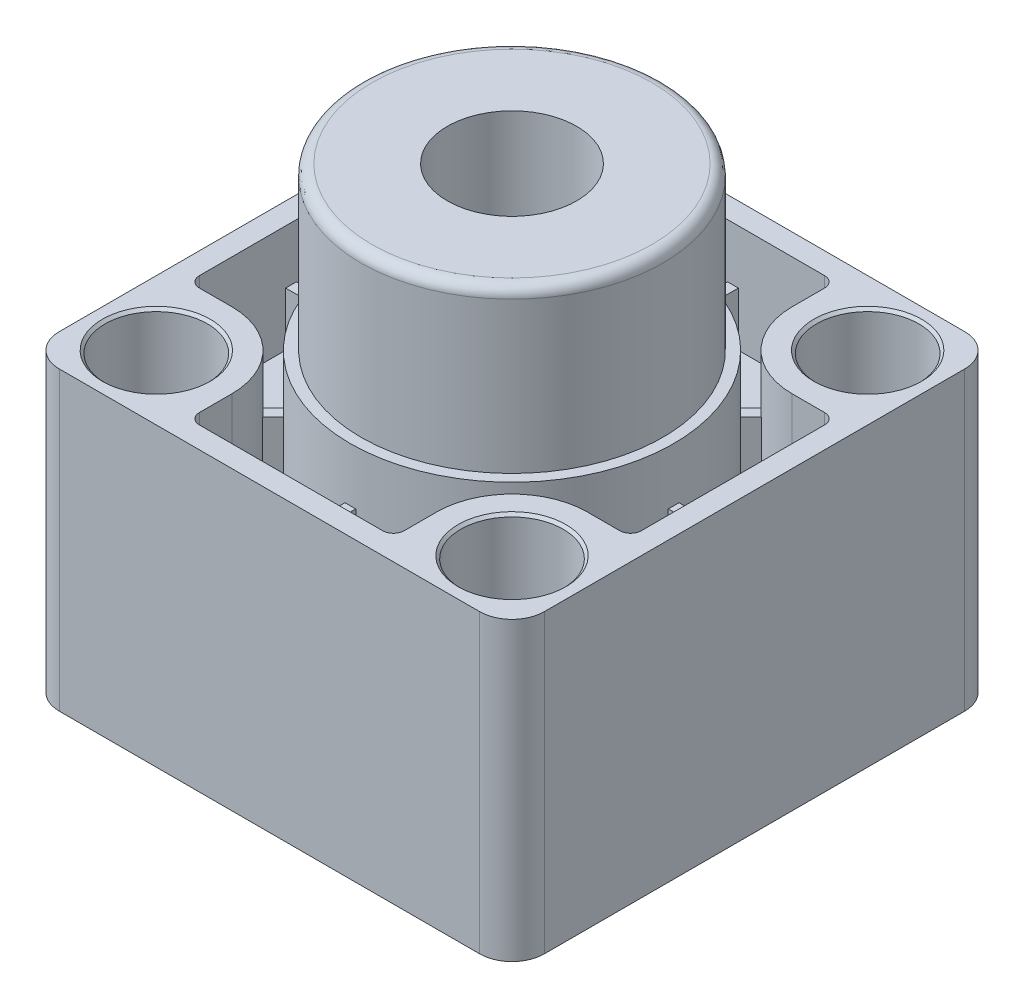
SolidWorks part; units mm, degrees
material "6061-T6 (SS)"
ref_plane "Front Plane" through (0, 0, 0) normal (0, 0, 1) x (1, 0, 0)
ref_plane "Top Plane" through (0, 0, 0) normal (0, 1, 0) x (1, 0, 0)
ref_plane "Right Plane" through (0, 0, 0) normal (1, 0, 0) x (0, 0, -1)
sketch "Sketch1" plane through (0, 0, 0) normal (0, 1, 0) x (1, 0, 0)
  line L1 (-19.5, -22.5) -> (19.5, -22.5)
  line L2 (-22.5, -19.5) -> (-22.5, 19.5)
  line L3 (-19.5, 22.5) -> (19.5, 22.5)
  line L4 (22.5, -19.5) -> (22.5, 19.5)
  line L5 (-22.5, -22.5) -> (22.5, 22.5) construction
  line L6 (-22.5, 22.5) -> (22.5, -22.5) construction
  arc A0 (-19.5, -22.5) -> (-22.5, -19.5) centre (-19.5, -19.5) cw
  arc A1 (19.5, -22.5) -> (22.5, -19.5) centre (19.5, -19.5) ccw
  arc A2 (19.5, 22.5) -> (22.5, 19.5) centre (19.5, 19.5) cw
  arc A3 (-22.5, 19.5) -> (-19.5, 22.5) centre (-19.5, 19.5) cw
  point P0 (0, 0)
  dimension "D2" = 3
  dimension "D1" = 45
extrude "Boss-Extrude1" add sketch "Sketch1" along normal blind 27.5
hole_wizard "CBORE for M6 Hex Socket Head Cap Screw1" positions "Sketch4" profile "Sketch3" counterbore size "M6" standard "DIN" end condition through all
sketch "Sketch4" plane through (0, 27.5, 0) normal (0, 1, 0) x (1, 0, 0)
  point P0 (-16.5, 16.5)
  point P2 (16.5, 16.5)
  point P4 (16.5, -16.5)
  point P6 (-16.5, -16.5)
  dimension "D1" = 33
  dimension "D2" = 16.5
  dimension "D3" = 16.5
  dimension "D4" = 16.5
sketch "Sketch3" plane through (-16.5, 27.5, -16.5) normal (1, 0, 0) x (0, 0, 1)
  line L0 (0, 0) -> (0, 27.5)
  line L1 (0, 27.5) -> (3.2, 27.5)
  line L3 (3.2, 27.5) -> (3.2, 15)
  line L4 (4.75, 15) -> (3.2, 15)
  line L5 (4.75, 15) -> (4.75, 0.25)
  line L6 (4.75, 0.25) -> (5, 0)
  line L7 (5, 0) -> (0, 0)
  line L8 (-4.75, 0.25) -> (-5, 0) construction
  line L11 (0, -6.35) -> (0, 107.95) construction
  dimension "Thru Hole Dia." = 6.4
  dimension "Thru Hole Depth" = 27.5
  dimension "C'Bore Dia." = 9.5
  dimension "C'Bore Depth" = 15
  dimension "Near C'Sink Dia." = 10
  dimension "Near C'Sink Angle" = 90
sketch "Sketch5" [suppressed] plane through (0, 27.5, 0) normal (0, 1, 0) x (1, 0, 0)
  line L4 (-9.5, 16.5) -> (-9.5, 20.5)
  line L5 (-16.5, 9.5) -> (-20.5, 9.5)
  line L6 (16.5, 9.5) -> (20.5, 9.5)
  line L7 (9.5, 16.5) -> (9.5, 20.5)
  line L8 (-19.5, -20.5) -> (19.5, -20.5)
  line L9 (20.5, -19.5) -> (20.5, 19.5)
  line L10 (19.5, 20.5) -> (-19.5, 20.5)
  line L11 (-20.5, 19.5) -> (-20.5, -19.5)
  line L12 (-19.5, -20.5) -> (19.5, -20.5)
  line L13 (20.5, -19.5) -> (20.5, 19.5)
  line L14 (19.5, 20.5) -> (-19.5, 20.5)
  line L15 (-20.5, 19.5) -> (-20.5, -19.5)
  line L16 (9.5, -16.5) -> (9.5, -20.5)
  line L17 (16.5, -9.5) -> (20.5, -9.5)
  line L18 (-16.5, -9.5) -> (-20.5, -9.5)
  line L19 (-9.5, -16.5) -> (-9.5, -20.5)
  circle A6 centre (-16.5, 16.5) radius 7
  arc A7 (-20.5, 10.7554) -> (-10.7554, 20.5) centre (-16.5, 16.5) ccw
  arc A8 (-20.5, -19.5) -> (-19.5, -20.5) centre (-19.5, -19.5) ccw
  arc A9 (19.5, -20.5) -> (20.5, -19.5) centre (19.5, -19.5) ccw
  arc A10 (20.5, 19.5) -> (19.5, 20.5) centre (19.5, 19.5) ccw
  arc A11 (-19.5, 20.5) -> (-20.5, 19.5) centre (-19.5, 19.5) ccw
  arc A12 (-20.5, -19.5) -> (-19.5, -20.5) centre (-19.5, -19.5) ccw
  arc A13 (19.5, -20.5) -> (20.5, -19.5) centre (19.5, -19.5) ccw
  arc A14 (20.5, 19.5) -> (19.5, 20.5) centre (19.5, 19.5) ccw
  arc A15 (-19.5, 20.5) -> (-20.5, 19.5) centre (-19.5, 19.5) ccw
  circle A39 centre (16.5, 16.5) radius 7
  arc A40 (10.7554, 20.5) -> (20.5, 10.7554) centre (16.5, 16.5) ccw
  circle A42 centre (-16.5, -16.5) radius 7
  arc A43 (-10.7554, -20.5) -> (-20.5, -10.7554) centre (-16.5, -16.5) ccw
  circle A44 centre (0, 0) radius 12
  circle A45 centre (16.5, -16.5) radius 7
  arc A46 (20.5, -10.7554) -> (10.7554, -20.5) centre (16.5, -16.5) ccw
  point P40 (0, 0)
  dimension "D7" = 24
  dimension "D6" = 4
  dimension "D1" = 2
  dimension "D2" = 2
  dimension "D3" = 2
  dimension "D4" = 2
  dimension "D5" = 2
extrude "Cut-Extrude1" [suppressed] cut sketch "Sketch5" against normal blind 10 contours A46 L17 L13 L6 A40 L7 L14 L4 A7 L5 L15 L18 A43 L19 L12 L16 A44
sketch "Sketch6" [suppressed] plane through (0, 17.5, 0) normal (0, 1, 0) x (1, 0, 0)
  line L0 (-20.5, 0) -> (12, 0)
  line L1 (-20.5, 9.5) -> (-20.5, -9.5) construction
  line L2 (0, 0) -> (0, 20.5)
  line L3 (9.5, 20.5) -> (-9.5, 20.5) construction
  line L4 (12, 0) -> (20.5, 0)
  line L5 (20.5, -9.5) -> (20.5, 9.5) construction
  line L6 (0, 0) -> (0, -20.5)
  line L7 (-9.5, -20.5) -> (9.5, -20.5) construction
  circle A1 centre (0, 0) radius 12 construction
extrude "Extrude-Thin2" [suppressed] add sketch "Sketch6" along normal blind 5 thin
draft "Draft1" [suppressed] type of draft neutral plane draft angle 4 faces to draft 1 parameters "D1"=4
sketch "Sketch7" [suppressed] plane through (0, 27.5, 0) normal (0, 1, 0) x (1, 0, 0)
  circle A2 centre (0, 0) radius 10
  circle A3 centre (0, 0) radius 10
  dimension "D1" = 2
extrude "Cut-Extrude2" [suppressed] cut sketch "Sketch7" against normal blind 1
sketch "Sketch8" plane through (0, 27.5, 0) normal (0, 1, 0) x (1, 0, 0)
  line L2 (-20.5, 19.5) -> (-20.5, -19.5)
  line L3 (-20.5, 9.5) -> (-20.5, 0)
  line L4 (0, 20.5) -> (0, 22.5) construction
  line L5 (19.5, 20.5) -> (-19.5, 20.5)
  line L6 (0, 20.5) -> (-9.5, 20.5)
  line L7 (19.5, 22.5) -> (-19.5, 22.5) construction
  line L8 (-22.5, 0) -> (-20.5, 0) construction
  line L9 (-22.5, 19.5) -> (-22.5, -19.5) construction
  line L10 (-9.5, 16.5) -> (-9.5, 20.5)
  line L11 (-16.5, 9.5) -> (-20.5, 9.5)
  line L12 (9.5, 20.5) -> (0, 20.5)
  line L13 (20.5, 0) -> (20.5, 9.5)
  line L14 (16.5, 9.5) -> (20.5, 9.5)
  line L15 (9.5, 16.5) -> (9.5, 20.5)
  line L16 (20.5, 0) -> (22.5, 0) construction
  line L17 (0, 22.5) -> (0, 20.5) construction
  line L18 (20.5, -9.5) -> (20.5, 0)
  line L19 (0, -20.5) -> (9.5, -20.5)
  line L20 (9.5, -16.5) -> (9.5, -20.5)
  line L21 (16.5, -9.5) -> (20.5, -9.5)
  line L22 (0, -20.5) -> (0, -22.5) construction
  line L23 (22.5, 0) -> (20.5, 0) construction
  line L24 (-9.5, -20.5) -> (0, -20.5)
  line L25 (-20.5, 0) -> (-20.5, -9.5)
  line L26 (-16.5, -9.5) -> (-20.5, -9.5)
  line L27 (-9.5, -16.5) -> (-9.5, -20.5)
  line L28 (-20.5, 0) -> (-22.5, 0) construction
  line L29 (0, -22.5) -> (0, -20.5) construction
  circle A0 centre (0, 0) radius 15
  arc A2 (9.5, 16.5) -> (16.5, 9.5) centre (16.5, 16.5) ccw
  circle A3 centre (-16.5, 16.5) radius 7
  arc A4 (-16.5, 9.5) -> (-9.5, 16.5) centre (-16.5, 16.5) ccw
  arc A5 (16.5, -9.5) -> (9.5, -16.5) centre (16.5, -16.5) ccw
  arc A6 (-9.5, -16.5) -> (-16.5, -9.5) centre (-16.5, -16.5) ccw
  point P51 (0, 0)
  dimension "D1" = 30
  dimension "D5" = 4
  dimension "D2" = 2
  dimension "D3" = 2
  dimension "D4" = 2
extrude "Cut-Extrude3" cut sketch "Sketch8" against normal blind 10 contours A6 L27 L24 L19 L20 A5 L21 L18 L13 L14 A2 L15 L12 L6 L10 A4 L11 L3 L25 L26 A0
sketch "Sketch9" plane through (0, 17.5, 0) normal (0, 1, 0) x (1, 0, 0)
  line L0 (0, 21.2588) -> (0, 13.5317)
  line L1 (0, 0) -> (-9.8763, 9.8763) construction
  line L2 (-9.8763, 9.8763) -> (0, 9.8763) construction
  line L3 (0, 9.8763) -> (0, 0) construction
  line L4 (-9.8763, 9.8763) -> (-12.0144, 12.0144)
  line L5 (21.2588, 0) -> (13.5317, 0)
  line L6 (9.8763, 9.8763) -> (12.0144, 12.0144)
  line L7 (9.8763, 9.8763) -> (9.8763, 0) construction
  line L8 (0, -21.2588) -> (0, -13.5317)
  line L9 (9.8763, -9.8763) -> (12.0144, -12.0144)
  line L10 (9.8763, -9.8763) -> (0, -9.8763) construction
  line L11 (-21.2588, 0) -> (-13.5317, 0)
  line L12 (-9.8763, -9.8763) -> (-12.0144, -12.0144)
  line L13 (-9.8763, -9.8763) -> (-9.8763, 0) construction
  point P25 (0, 0)
  dimension "D1" = 45
  dimension "D2" = 4
extrude "Extrude-Thin3" add sketch "Sketch9" along normal blind 5 thin thin type mid plane wall 1
fillet "Fillet1" radius 1 8 edges at (20.5, 22.5, 9.5) (9.5, 22.5, 20.5) (-9.5, 22.5, 20.5) (-20.5, 22.5, 9.5) (-20.5, 22.5, -9.5) (20.5, 22.5, -9.5) (9.5, 22.5, -20.5) (-9.5, 22.5, -20.5)
sketch "Sketch10" plane through (0, 27.5, 0) normal (0, 1, 0) x (1, 0, 0)
  circle A0 centre (0, 0) radius 14
  dimension "D1" = 28
extrude "Boss-Extrude2" add sketch "Sketch10" along normal blind 15
fillet "Fillet2" radius 1 1 edges at (0, 42.5, 14)
sketch "Sketch11" plane through (0, 42.5, 0) normal (0, 1, 0) x (1, 0, 0)
  circle A0 centre (0, 0) radius 6
  dimension "D1" = 12
extrude "Cut-Extrude4" cut sketch "Sketch11" against normal through all
sketch "Sketch12" plane through (0, 0, 0) normal (0, -1, 0) x (1, 0, 0)
  circle A0 centre (0, 0) radius 16
  circle A1 centre (0, 0) radius 18
  dimension "D1" = 32
  dimension "D2" = 36
extrude "Boss-Extrude3" add sketch "Sketch12" along normal blind 5
sketch "Sketch13" plane through (0, 0, -22.5) normal (0, 0, -1) x (-1, 0, 0)
  line L0 (-19.5, 0) -> (19.5, 0) construction
  circle A0 centre (5.5, 13.75) radius 3.175
  dimension "D1" = 6.35
  dimension "D2" = 13.75
  dimension "D3" = 5.5
extrude "Cut-Extrude5" [suppressed] cut sketch "Sketch13" against normal blind 10
chamfer "Chamfer1" [suppressed] distance 0.5 angle 45
sketch "Sketch14" plane through (0, 0, -22.5) normal (0, 0, -1) x (-1, 0, 0)
  line L0 (-19.5, 27.5) -> (19.5, 27.5) construction
  circle A0 centre (-5.5, 13.75) radius 3.175
  dimension "D1" = 6.35
  dimension "D2" = 13.75
  dimension "D3" = 5.5
extrude "Cut-Extrude6" cut sketch "Sketch14" against normal blind 10
chamfer "Chamfer2" distance 0.5 angle 45 1 edges at (2.325, 13.75, -22.5)
